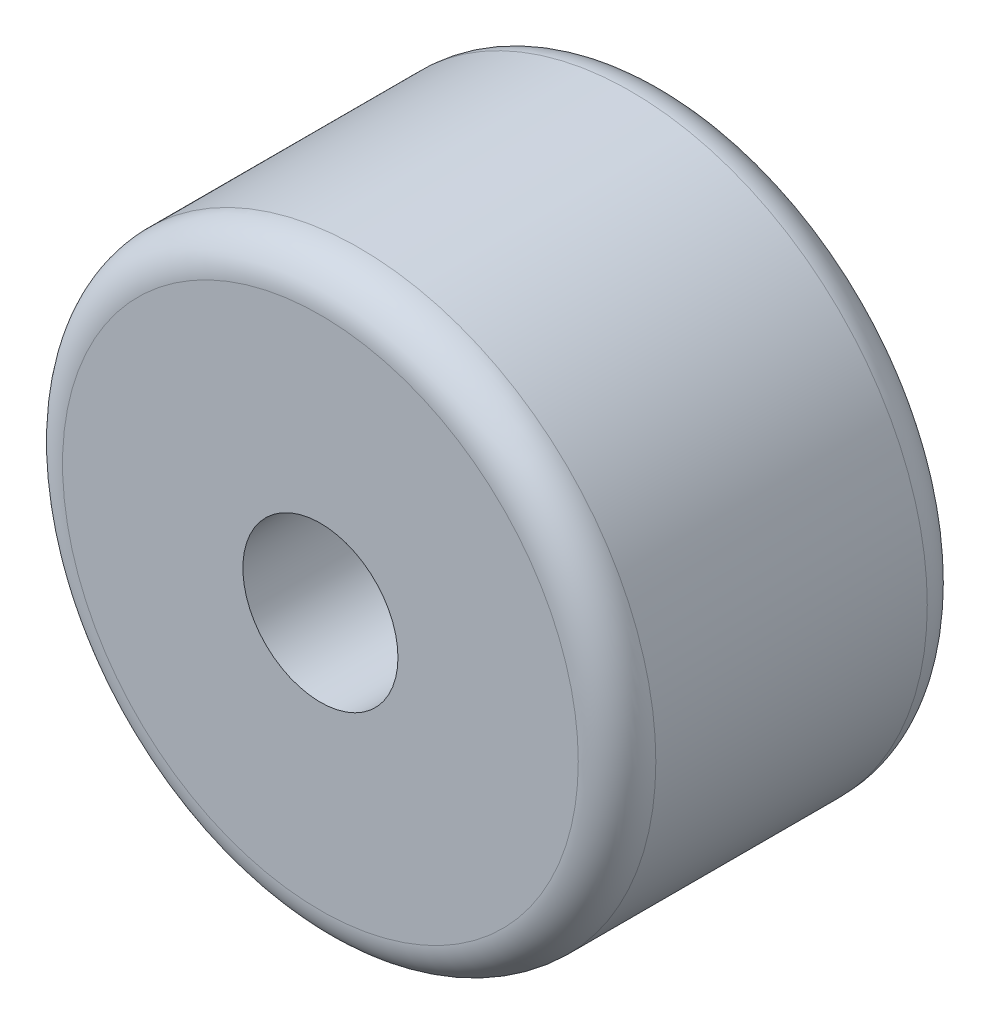
SolidWorks part; units mm, degrees
material "ABS"
ref_plane "Front Plane" through (0, 0, 0) normal (0, 0, 1) x (1, 0, 0)
ref_plane "Top Plane" through (0, 0, 0) normal (0, 1, 0) x (1, 0, 0)
ref_plane "Right Plane" through (0, 0, 0) normal (1, 0, 0) x (0, 0, -1)
sketch "Sketch1" plane through (0, 0, 0) normal (0, 0, 1) x (1, 0, 0)
  circle A0 centre (0, 0) radius 7.65
  dimension "D1" = 15.3
extrude "Boss-Extrude1" add sketch "Sketch1" along normal blind 9
sketch "Sketch2" plane through (0, 0, 9) normal (0, 0, 1) x (1, 0, 0)
  circle A0 centre (0, 0) radius 2
  dimension "D1" = 4
extrude "Cut-Extrude2" cut sketch "Sketch2" against normal blind 9
fillet "Fillet1" radius 1 2 edges at (7.65, 0, 0) (7.65, 0, 9)
